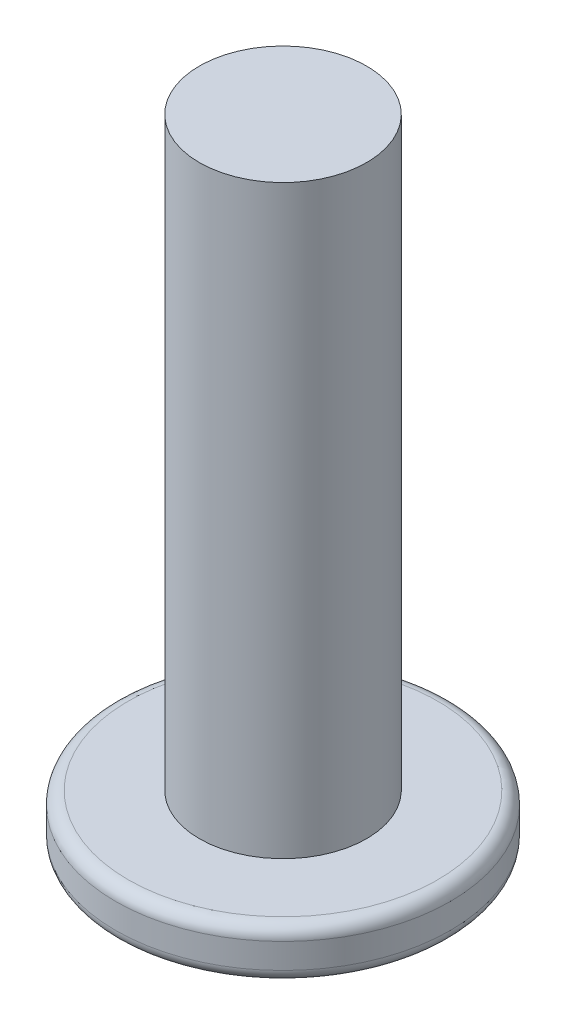
SolidWorks part; units mm, degrees
ref_plane "Front Plane" through (0, 0, 0) normal (0, 0, 1) x (1, 0, 0)
ref_plane "Top Plane" through (0, 0, 0) normal (0, 1, 0) x (1, 0, 0)
ref_plane "Right Plane" through (0, 0, 0) normal (1, 0, 0) x (0, 0, -1)
sketch "Sketch1" plane through (0, 0, 0) normal (0, 1, 0) x (1, 0, 0)
  circle A0 centre (0, 0) radius 4
  dimension "D1" = 8
extrude "Boss-Extrude1" add sketch "Sketch1" along normal blind 1.2
sketch "Sketch2" plane through (0, 1.2, 0) normal (0, 1, 0) x (1, 0, 0)
  circle A0 centre (0, 0) radius 2
  dimension "D1" = 4
extrude "Boss-Extrude2" add sketch "Sketch2" along normal blind 14
fillet "Fillet2" radius 0.3 2 edges at (0, 0, 4) (0, 1.2, 4)
sketch "Sketch3" plane through (0, 0, 0) normal (0, -1, 0) x (1, 0, 0)
  line L1 (1.4434, 0) -> (0.7217, 1.25)
  line L2 (0.7217, 1.25) -> (-0.7217, 1.25)
  line L3 (-0.7217, 1.25) -> (-1.4434, 0)
  line L4 (-1.4434, 0) -> (-0.7217, -1.25)
  line L5 (-0.7217, -1.25) -> (0.7217, -1.25)
  line L6 (0.7217, -1.25) -> (1.4434, 0)
  circle A0 centre (0, 0) radius 1.25 construction
  dimension "D1" = 2.5
extrude "Cut-Extrude1" cut sketch "Sketch3" against normal blind 0.6
